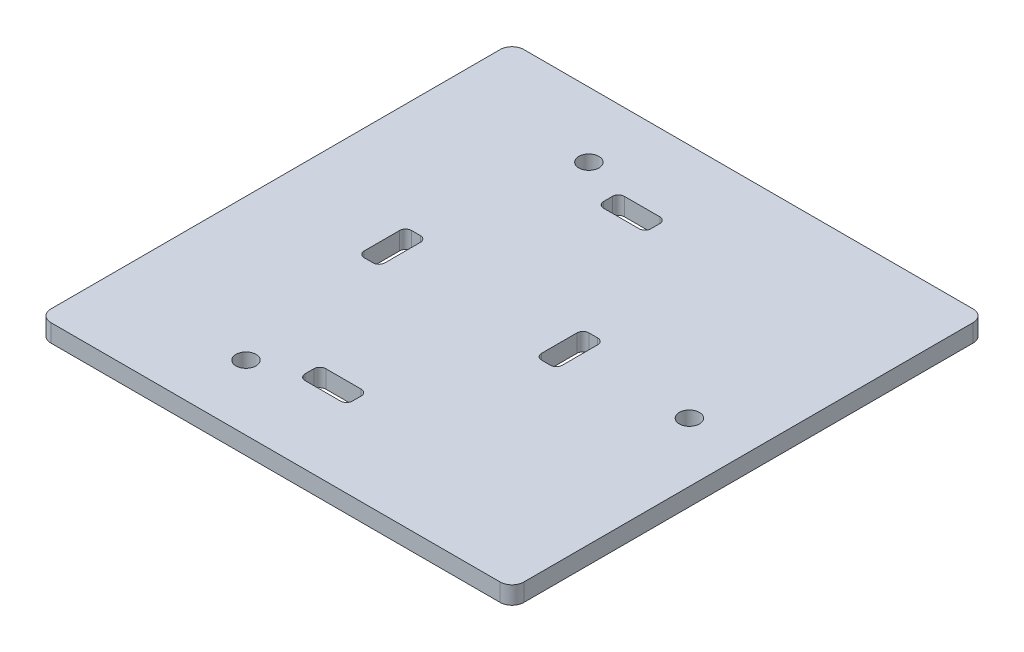
SolidWorks part; units mm, degrees
ref_plane "Front Plane" through (0, 0, 0) normal (0, 0, 1) x (1, 0, 0)
ref_plane "Top Plane" through (0, 0, 0) normal (0, 1, 0) x (1, 0, 0)
ref_plane "Right Plane" through (0, 0, 0) normal (1, 0, 0) x (0, 0, -1)
sketch "Sketch1" plane through (0, 0, 0) normal (0, 1, 0) x (1, 0, 0)
  line L1 (-40, 40) -> (40, 40)
  line L2 (-40, 40) -> (-40, -40)
  line L3 (-40, -40) -> (40, -40)
  line L4 (40, 40) -> (40, -40)
  line L5 (-40, 40) -> (40, -40) construction
  line L6 (-40, -40) -> (40, 40) construction
  point P0 (0, 0)
  dimension "D1" = 80
  dimension "D2" = 80
extrude "Boss-Extrude1" add sketch "Sketch1" along normal blind 3
sketch "Sketch5" plane through (0, 0, 0) normal (0, 1, 0) x (1, 0, 0)
  line L0 (14.25, 10) -> (10.25, 10) construction
  line L1 (8, 4) -> (11.5, 4)
  line L2 (8, 4) -> (8, -4)
  line L3 (8, -4) -> (11.5, -4)
  line L4 (11.5, 4) -> (11.5, -4)
  line L5 (8, 4) -> (11.5, -4) construction
  line L6 (8, -4) -> (11.5, 4) construction
  line L8 (40, -40) -> (40, 40) construction
  line L9 (40, 40) -> (-40, 40) construction
  line L10 (-22, 4) -> (-18.5, 4)
  line L11 (-22, 4) -> (-22, -4)
  line L12 (-22, -4) -> (-18.5, -4)
  line L13 (-18.5, 4) -> (-18.5, -4)
  line L14 (-22, 4) -> (-18.5, -4) construction
  line L15 (-22, -4) -> (-18.5, 4) construction
  line L17 (-40, -40) -> (40, -40) construction
  line L18 (-9, 27) -> (-1, 27)
  line L19 (-9, 27) -> (-9, 23.5)
  line L20 (-9, 23.5) -> (-1, 23.5)
  line L21 (-1, 27) -> (-1, 23.5)
  line L22 (-9, 27) -> (-1, 23.5) construction
  line L23 (-9, 23.5) -> (-1, 27) construction
  line L24 (-9, -23.5) -> (-1, -23.5)
  line L25 (-9, -23.5) -> (-9, -27)
  line L26 (-9, -27) -> (-1, -27)
  line L27 (-1, -23.5) -> (-1, -27)
  line L28 (-9, -23.5) -> (-1, -27) construction
  line L29 (-9, -27) -> (-1, -23.5) construction
  line L31 (9.75, 0) -> (30, 0) construction
  line L32 (-40, 40) -> (-40, -40) construction
  circle A0 centre (30, 0) radius 1.7
  circle A1 centre (-16, 29) radius 1.7
  circle A2 centre (-16, -29) radius 1.7
  point P0 (9.75, 0)
  point P7 (-20.25, 0)
  point P14 (-20.25, 4)
  point P17 (-1, 25.25)
  point P18 (-5, -25.25)
  point P19 (-5, 25.25)
  dimension "D17" = 3.4
  dimension "D19" = 3.4
  dimension "D22" = 3.4
  dimension "D1" = 8
  dimension "D2" = 6
  dimension "D3" = 28.5
  dimension "D4" = 3.5
  dimension "D5" = 30
  dimension "D6" = 8
  dimension "D7" = 3.5
  dimension "D8" = 36
  dimension "D9" = 13
  dimension "D10" = 3.5
  dimension "D11" = 8
  dimension "D12" = 41
  dimension "D13" = 13
  dimension "D14" = 8
  dimension "D15" = 3.5
  dimension "D16" = 41
  dimension "D18" = 10
  dimension "D20" = 11
  dimension "D21" = 24
  dimension "D23" = 11
  dimension "D24" = 24
extrude "Cut-Extrude5" cut sketch "Sketch5" along normal up to surface (3 mm away) up to face at (0, 3, 0)
fillet "Fillet1" radius 1 4 edges at (11.5, 1.5, 4) (8, 1.5, 4) (8, 1.5, -4) (11.5, 1.5, -4)
fillet "Fillet2" radius 1 12 edges at (-9, 1.5, -23.5) (-1, 1.5, -23.5) (-1, 1.5, -27) (-9, 1.5, -27) (-22, 1.5, 4) (-22, 1.5, -4) (-18.5, 1.5, -4) (-18.5, 1.5, 4) (-9, 1.5, 27) (-1, 1.5, 27) (-1, 1.5, 23.5) (-9, 1.5, 23.5)
fillet "Fillet3" radius 2 4 edges at (40, 1.5, 40) (40, 1.5, -40) (-40, 1.5, 40) (-40, 1.5, -40)
